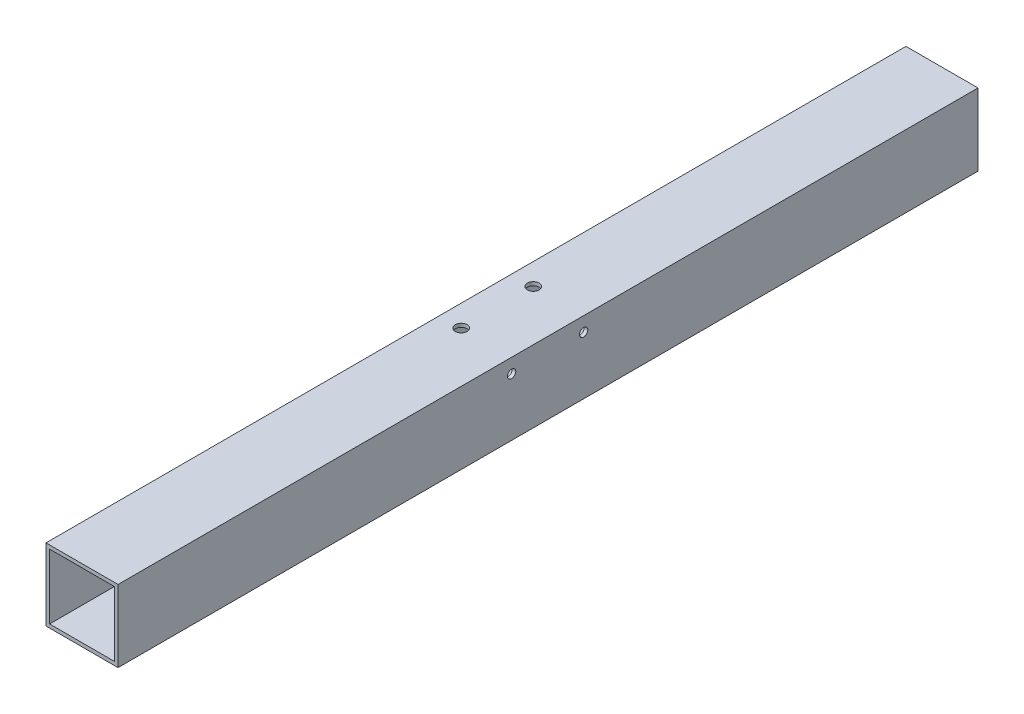
SolidWorks part; units mm, degrees
ref_plane "Front Plane" through (0, 0, 0) normal (0, 0, 1) x (1, 0, 0)
ref_plane "Top Plane" through (0, 0, 0) normal (0, 1, 0) x (1, 0, 0)
ref_plane "Right Plane" through (0, 0, 0) normal (1, 0, 0) x (0, 0, -1)
sketch "Sketch1" plane through (0, 0, 0) normal (0, 0, 1) x (1, 0, 0)
  line L1 (-9, -9) -> (9, -9)
  line L2 (-9, -9) -> (-9, 9)
  line L3 (-9, 9) -> (9, 9)
  line L4 (9, -9) -> (9, 9)
  line L5 (-9, -9) -> (9, 9) construction
  line L6 (-9, 9) -> (9, -9) construction
  line L7 (-10, -10) -> (10, -10)
  line L8 (-10, -10) -> (-10, 10)
  line L9 (-10, 10) -> (10, 10)
  line L10 (10, -10) -> (10, 10)
  line L11 (-10, -10) -> (10, 10) construction
  line L12 (-10, 10) -> (10, -10) construction
  point P0 (0, 0)
  point P6 (0, 0)
  dimension "D1" = 18
  dimension "D2" = 20
extrude "Boss-Extrude2" add sketch "Sketch1" along normal blind 238.73
sketch "Sketch3" plane through (0, 10, 0) normal (0, 1, 0) x (1, 0, 0)
  circle A0 centre (-4, -109.46) radius 1.65
  circle A1 centre (-4, -129.46) radius 1.65
  dimension "D1" = 3.3
  dimension "D2" = 3.3
  dimension "D3" = 6
  dimension "D4" = 109.46
  dimension "D5" = 129.46
  dimension "D6" = 6
extrude "Cut-Extrude1" cut sketch "Sketch3" against normal through all both and the other way through all
sketch "Sketch4" plane through (-10, 0, 0) normal (-1, 0, 0) x (0, 0, 1)
  line L1 (238.73, 10) -> (238.73, -10) construction
  circle A0 centre (129.47, 6) radius 1.15
  circle A1 centre (109.47, 6) radius 1.15
  dimension "D1" = 2.3
  dimension "D2" = 2.3
  dimension "D3" = 4
  dimension "D4" = 4
  dimension "D5" = 109.26
  dimension "D6" = 129.26
extrude "Cut-Extrude2" cut sketch "Sketch4" against normal through all both and the other way through all
